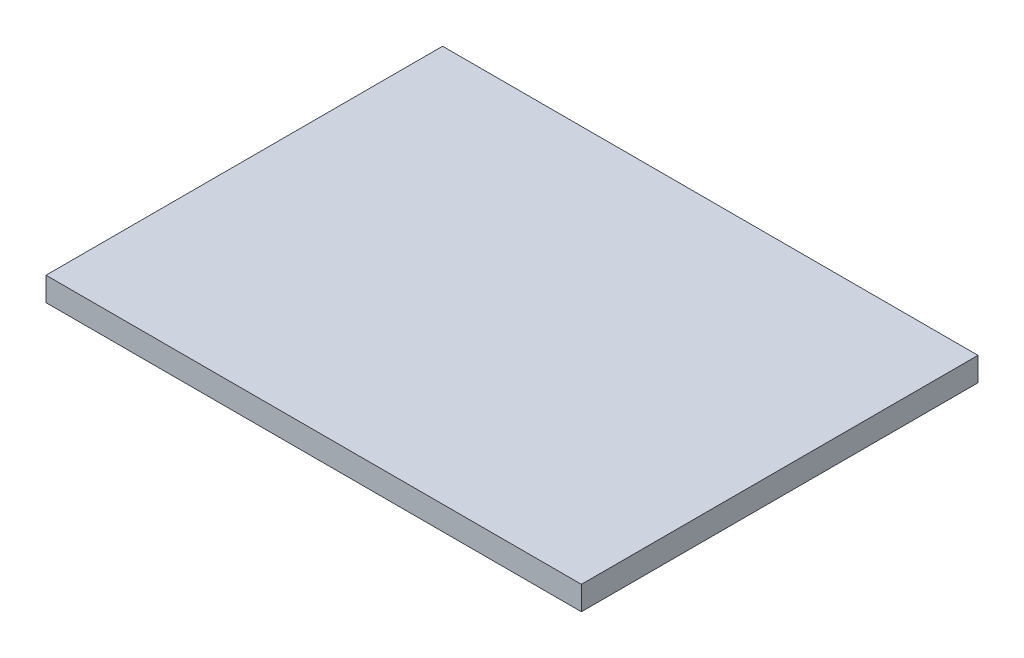
SolidWorks part; units mm, degrees
ref_plane "前视基准面" through (0, 0, 0) normal (0, 0, 1) x (1, 0, 0)
ref_plane "上视基准面" through (0, 0, 0) normal (0, 1, 0) x (1, 0, 0)
ref_plane "右视基准面" through (0, 0, 0) normal (1, 0, 0) x (0, 0, -1)
sketch "草图1" plane through (0, 0, 0) normal (0, 1, 0) x (1, 0, 0)
  line L1 (0, 0) -> (27, 0)
  line L2 (0, 0) -> (0, 20)
  line L3 (0, 20) -> (27, 20)
  line L4 (27, 0) -> (27, 20)
  dimension "D1" = 27
  dimension "D2" = 20
extrude "凸台-拉伸1" add sketch "草图1" along normal blind 1.2
